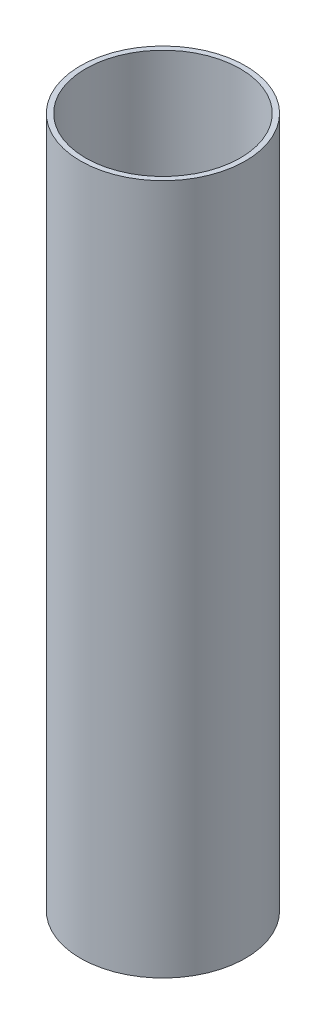
SolidWorks part; units mm, degrees
material "Fuzed Silica"
ref_plane "Front Plane" through (0, 0, 0) normal (0, 0, 1) x (1, 0, 0)
ref_plane "Top Plane" through (0, 0, 0) normal (0, 1, 0) x (1, 0, 0)
ref_plane "Right Plane" through (0, 0, 0) normal (1, 0, 0) x (0, 0, -1)
sketch "Sketch1" plane through (0, 0, 0) normal (0, 1, 0) x (1, 0, 0)
  circle A0 centre (0, 0) radius 37.5
  circle A1 centre (0, 0) radius 40
  dimension "D1" = 80
  dimension "D2" = 75
extrude "Boss-Extrude1" add sketch "Sketch1" along normal blind 334.8
